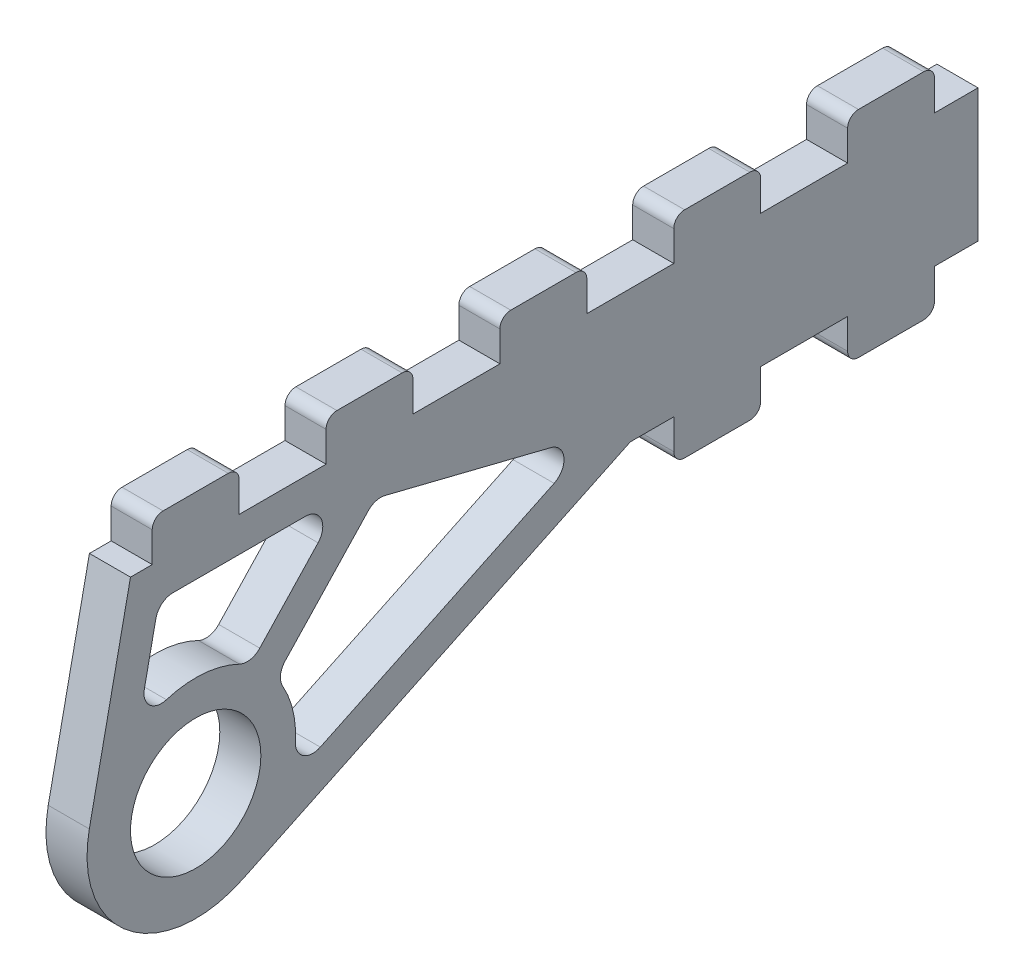
SolidWorks part; units mm, degrees
ref_plane "Front Plane" through (0, 0, 0) normal (0, 0, 1) x (1, 0, 0)
ref_plane "Top Plane" through (0, 0, 0) normal (0, 1, 0) x (1, 0, 0)
ref_plane "Right Plane" through (0, 0, 0) normal (1, 0, 0) x (0, 0, -1)
sketch "Sketch1" plane through (0, 0, 0) normal (1, 0, 0) x (0, 0, -1)
  line L0 (-41.4563, 38.1) -> (38.3452, 38.1) construction
  line L1 (-15.541, 3.2395) -> (-9.525, 32.1)
  line L2 (38.9021, 32.1) -> (-38.9021, 32.1) construction
  line L3 (38.9021, 32.1) -> (38.9021, 38.1) construction
  line L4 (38.9021, 38.1) -> (-38.9021, 38.1) construction
  line L5 (-38.9021, 32.1) -> (-38.9021, 38.1) construction
  line L6 (38.9021, 32.1) -> (-38.9021, 38.1) construction
  line L7 (38.9021, 38.1) -> (-38.9021, 32.1) construction
  line L8 (0, 7.3323) -> (-6.35, 3.6662) construction
  line L9 (-6.35, 3.6662) -> (-6.35, -3.6662) construction
  line L10 (-6.35, -3.6662) -> (0, -7.3323) construction
  line L11 (0, -7.3323) -> (6.35, -3.6662) construction
  line L12 (6.35, -3.6662) -> (6.35, 3.6662) construction
  line L13 (6.35, 3.6662) -> (0, 7.3323) construction
  line L14 (-9.525, 32.1) -> (63.5, 32.1)
  line L15 (0, -15.875) -> (63.5, -15.875)
  line L16 (63.5, -15.875) -> (63.5, 32.1)
  line L18 (157.9971, 6.7) -> (88.9, 6.7) construction
  line L19 (157.9971, 6.7) -> (157.9971, 12.7) construction
  line L20 (157.9971, 12.7) -> (88.9, 12.7) construction
  line L21 (88.9, 6.7) -> (88.9, 12.7) construction
  line L22 (157.9971, 6.7) -> (88.9, 12.7) construction
  line L23 (157.9971, 12.7) -> (88.9, 6.7) construction
  circle A0 centre (0, 0) radius 9.525
  arc A1 (-15.541, 3.2395) -> (0, -15.875) centre (0, 0) ccw
  circle A2 centre (0, 0) radius 25.4 construction
  circle A3 centre (0, 0) radius 6.35 construction
  arc A4 (0, -15.875) -> (-15.541, 3.2395) centre (0, 0) ccw construction
  point P3 (123.4486, 9.7)
  point P7 (0, 35.1)
  point P28 (88.9, 9.7)
  dimension "D1" = 19.05
  dimension "D2" = 6.35
  dimension "D4" = 50.8
  dimension "D3" = 38.1
  dimension "D5" = 6
  dimension "D6" = 12.7
  dimension "D7" = 9.525
  dimension "D8" = 63.5
  dimension "D9" = 25.4
  dimension "D10" = 88.9
extrude "Boss-Extrude1" add sketch "Sketch1" along normal mid plane 6
sketch "Sketch2" plane through (3, 0, 0) normal (1, 0, 0) x (0, 0, -1)
  line L0 (6.8345, -14.3285) -> (63.5, 12.7)
  line L2 (63.5, -15.875) -> (63.5, 32.1) construction
  line L5 (63.5, 12.7) -> (63.5, -15.875)
  line L8 (63.5, -15.875) -> (0, -15.875)
  line L11 (0, -15.875) -> (63.5, -15.875) construction
  line L12 (157.9971, 12.7) -> (88.9, 12.7) construction
  line L22 (0, 0) -> (15.49, 0) construction
  circle A10 centre (0, 0) radius 15.875 construction
  arc A11 (6.8345, -14.3285) -> (0, -15.875) centre (0, 0) cw
  arc A13 (-15.541, 3.2395) -> (0, -15.875) centre (0, 0) ccw construction
extrude "Cut-Extrude1" cut sketch "Sketch2" against normal through all
sketch "Sketch4" plane through (3, 0, 0) normal (1, 0, 0) x (0, 0, -1)
  line L0 (157.9971, 12.7) -> (88.9, 12.7) construction
  line L1 (63.5, 32.1) -> (114.3, 32.1)
  line L2 (63.5, 32.1) -> (63.5, 12.7)
  line L3 (63.5, 12.7) -> (114.3, 12.7)
  line L4 (114.3, 32.1) -> (114.3, 12.7)
  line L5 (88.9, 6.7) -> (88.9, 12.7) construction
  dimension "D1" = 25.4
extrude "Boss-Extrude3" add sketch "Sketch4" against normal up to surface (6 mm away) up to face at (-3, 11.7739, -20.6636)
sketch "Sketch3" plane through (0, 32.1, 0) normal (0, 1, 0) x (1, 0, 0)
  line L0 (3, 114.3) -> (3, -9.525) construction
  line L1 (-3, -6.35) -> (3, -6.35)
  line L2 (-3, -6.35) -> (-3, 6.35)
  line L3 (-3, 6.35) -> (3, 6.35)
  line L4 (3, -6.35) -> (3, 6.35)
  line L5 (-3, -6.35) -> (3, 6.35) construction
  line L6 (-3, 6.35) -> (3, -6.35) construction
  point P0 (0, 0)
  dimension "D1" = 12.7
extrude "Boss-Extrude2" add sketch "Sketch3" along normal blind 6
fillet "Fillet1" radius 1.5875 2 edges at (0, 38.1, -6.35) (0, 38.1, 6.35)
pattern_linear "LPattern1" count 5 spacing 25.4 along (0, 0, -1) of "Boss-Extrude2", "Fillet1"
sketch "Sketch5" plane through (-3, 0, 0) normal (-1, 0, 0) x (0, 0, 1)
  line L0 (-114.3, 12.7) -> (-63.5, 12.7) construction
  line L1 (-69.85, 12.7) -> (-82.55, 12.7)
  line L2 (-69.85, 12.7) -> (-69.85, 6.7)
  line L3 (-69.85, 6.7) -> (-82.55, 6.7)
  line L4 (-82.55, 12.7) -> (-82.55, 6.7)
  line L5 (-69.85, 36.5125) -> (-69.85, 32.1) construction
  line L6 (-82.55, 36.5125) -> (-82.55, 32.1) construction
  dimension "D1" = 6
extrude "Boss-Extrude4" add sketch "Sketch5" against normal up to surface (6 mm away) up to face at (3, 31.7217, -49.7894)
fillet "Fillet2" radius 1.5875 2 edges at (0, 6.7, -69.85) (0, 6.7, -82.55)
pattern_linear "LPattern2" count 2 spacing 25.4 along (0, 0, -1) of "Boss-Extrude4", "Fillet2"
sketch "Sketch6" plane through (3, 0, 0) normal (1, 0, 0) x (0, 0, -1)
  line L0 (-5.3947, 27.02) -> (-10.5678, 2.2029)
  line L1 (4.6474, -9.7434) -> (62.3505, 17.78)
  line L2 (62.3505, 17.78) -> (74.93, 17.78)
  line L3 (74.93, 17.78) -> (74.93, 11.78)
  line L4 (74.93, 11.78) -> (77.47, 11.78)
  line L5 (77.47, 11.78) -> (77.47, 17.78)
  line L6 (77.47, 17.78) -> (100.33, 17.78)
  line L7 (100.33, 17.78) -> (100.33, 11.78)
  line L8 (100.33, 11.78) -> (102.87, 11.78)
  line L9 (102.87, 11.78) -> (102.87, 17.78)
  line L10 (102.87, 17.78) -> (109.22, 17.78)
  line L11 (109.22, 17.78) -> (109.22, 27.02)
  line L12 (109.22, 27.02) -> (102.87, 27.02)
  line L13 (102.87, 27.02) -> (102.87, 33.02)
  line L14 (102.87, 33.02) -> (100.33, 33.02)
  line L15 (100.33, 33.02) -> (100.33, 27.02)
  line L16 (100.33, 27.02) -> (77.47, 27.02)
  line L17 (77.47, 27.02) -> (77.47, 33.02)
  line L18 (77.47, 33.02) -> (74.93, 33.02)
  line L19 (74.93, 33.02) -> (74.93, 27.02)
  line L20 (74.93, 27.02) -> (52.07, 27.02)
  line L21 (52.07, 27.02) -> (52.07, 33.02)
  line L22 (52.07, 33.02) -> (49.53, 33.02)
  line L23 (49.53, 33.02) -> (49.53, 27.02)
  line L24 (49.53, 27.02) -> (26.67, 27.02)
  line L25 (26.67, 27.02) -> (26.67, 33.02)
  line L26 (26.67, 33.02) -> (24.13, 33.02)
  line L27 (24.13, 33.02) -> (24.13, 27.02)
  line L28 (24.13, 27.02) -> (1.27, 27.02)
  line L29 (1.27, 27.02) -> (1.27, 33.02)
  line L30 (1.27, 33.02) -> (-1.27, 33.02)
  line L31 (-1.27, 33.02) -> (-1.27, 27.02)
  line L32 (-1.27, 27.02) -> (-5.3947, 27.02)
  line L33 (95.25, 12.7) -> (95.25, 8.2875)
  line L34 (96.8375, 6.7) -> (106.3625, 6.7)
  line L35 (107.95, 8.2875) -> (107.95, 12.7)
  line L36 (107.95, 12.7) -> (114.3, 12.7)
  line L37 (114.3, 12.7) -> (114.3, 32.1)
  line L38 (114.3, 32.1) -> (107.95, 32.1)
  line L39 (107.95, 32.1) -> (107.95, 36.5125)
  line L40 (106.3625, 38.1) -> (96.8375, 38.1)
  line L41 (95.25, 36.5125) -> (95.25, 32.1)
  line L42 (95.25, 32.1) -> (82.55, 32.1)
  line L43 (82.55, 32.1) -> (82.55, 36.5125)
  line L44 (80.9625, 38.1) -> (71.4375, 38.1)
  line L45 (69.85, 36.5125) -> (69.85, 32.1)
  line L46 (69.85, 32.1) -> (57.15, 32.1)
  line L47 (57.15, 32.1) -> (57.15, 36.5125)
  line L48 (55.5625, 38.1) -> (46.0375, 38.1)
  line L49 (44.45, 36.5125) -> (44.45, 32.1)
  line L50 (44.45, 32.1) -> (31.75, 32.1)
  line L51 (31.75, 32.1) -> (31.75, 36.5125)
  line L52 (30.1625, 38.1) -> (20.6375, 38.1)
  line L53 (19.05, 36.5125) -> (19.05, 32.1)
  line L54 (19.05, 32.1) -> (6.35, 32.1)
  line L55 (6.35, 32.1) -> (6.35, 36.5125)
  line L56 (4.7625, 38.1) -> (-4.7625, 38.1)
  line L57 (-6.35, 36.5125) -> (-6.35, 32.1)
  line L58 (-6.35, 32.1) -> (-9.525, 32.1)
  line L59 (-9.525, 32.1) -> (-15.541, 3.2395)
  line L60 (6.8345, -14.3285) -> (63.5, 12.7)
  line L61 (63.5, 12.7) -> (69.85, 12.7)
  line L62 (69.85, 12.7) -> (69.85, 8.2875)
  line L63 (71.4375, 6.7) -> (80.9625, 6.7)
  line L64 (82.55, 8.2875) -> (82.55, 12.7)
  line L65 (82.55, 12.7) -> (95.25, 12.7)
  line L66 (95.25, 12.7) -> (95.25, 8.2875)
  line L67 (96.8375, 6.7) -> (106.3625, 6.7)
  line L68 (107.95, 8.2875) -> (107.95, 12.7)
  line L69 (107.95, 12.7) -> (114.3, 12.7)
  line L70 (114.3, 12.7) -> (114.3, 32.1)
  line L71 (114.3, 32.1) -> (107.95, 32.1)
  line L72 (107.95, 32.1) -> (107.95, 36.5125)
  line L73 (106.3625, 38.1) -> (96.8375, 38.1)
  line L74 (95.25, 36.5125) -> (95.25, 32.1)
  line L75 (95.25, 32.1) -> (82.55, 32.1)
  line L76 (82.55, 32.1) -> (82.55, 36.5125)
  line L77 (80.9625, 38.1) -> (71.4375, 38.1)
  line L78 (69.85, 36.5125) -> (69.85, 32.1)
  line L79 (69.85, 32.1) -> (57.15, 32.1)
  line L80 (57.15, 32.1) -> (57.15, 36.5125)
  line L81 (55.5625, 38.1) -> (46.0375, 38.1)
  line L82 (44.45, 36.5125) -> (44.45, 32.1)
  line L83 (44.45, 32.1) -> (31.75, 32.1)
  line L84 (31.75, 32.1) -> (31.75, 36.5125)
  line L85 (30.1625, 38.1) -> (20.6375, 38.1)
  line L86 (19.05, 36.5125) -> (19.05, 32.1)
  line L87 (19.05, 32.1) -> (6.35, 32.1)
  line L88 (6.35, 32.1) -> (6.35, 36.5125)
  line L89 (4.7625, 38.1) -> (-4.7625, 38.1)
  line L90 (-6.35, 36.5125) -> (-6.35, 32.1)
  line L91 (-6.35, 32.1) -> (-9.525, 32.1)
  line L92 (-9.525, 32.1) -> (-15.541, 3.2395)
  line L93 (6.8345, -14.3285) -> (63.5, 12.7)
  line L94 (63.5, 12.7) -> (69.85, 12.7)
  line L95 (69.85, 12.7) -> (69.85, 8.2875)
  line L96 (71.4375, 6.7) -> (80.9625, 6.7)
  line L97 (82.55, 8.2875) -> (82.55, 12.7)
  line L98 (82.55, 12.7) -> (95.25, 12.7)
  line L99 (0, 0) -> (25.3883, 27.02) construction
  line L100 (25.3883, 27.02) -> (62.3505, 17.78) construction
  line L101 (1.8511, -1.7393) -> (26.2186, 24.1943)
  line L102 (26.2186, 24.1943) -> (61.7345, 15.3158)
  line L103 (-1.8511, 1.7393) -> (24.5581, 29.8457)
  line L104 (24.5581, 29.8457) -> (62.9665, 20.2442)
  line L105 (-1.27, 27.02) -> (1.27, 27.02)
  circle A0 centre (0, 0) radius 9.525 construction
  circle A1 centre (0, 0) radius 9.525
  arc A2 (-10.5678, 2.2029) -> (4.6474, -9.7434) centre (0, 0) ccw
  arc A3 (74.93, 11.78) -> (74.93, 11.78) centre (74.93, 11.78) ccw
  arc A4 (77.47, 11.78) -> (77.47, 11.78) centre (77.47, 11.78) ccw
  arc A5 (100.33, 11.78) -> (100.33, 11.78) centre (100.33, 11.78) ccw
  arc A6 (102.87, 11.78) -> (102.87, 11.78) centre (102.87, 11.78) ccw
  arc A7 (102.87, 33.02) -> (102.87, 33.02) centre (102.87, 33.02) ccw
  arc A8 (100.33, 33.02) -> (100.33, 33.02) centre (100.33, 33.02) ccw
  arc A9 (77.47, 33.02) -> (77.47, 33.02) centre (77.47, 33.02) ccw
  arc A10 (74.93, 33.02) -> (74.93, 33.02) centre (74.93, 33.02) ccw
  arc A11 (52.07, 33.02) -> (52.07, 33.02) centre (52.07, 33.02) ccw
  arc A12 (49.53, 33.02) -> (49.53, 33.02) centre (49.53, 33.02) ccw
  arc A13 (26.67, 33.02) -> (26.67, 33.02) centre (26.67, 33.02) ccw
  arc A14 (24.13, 33.02) -> (24.13, 33.02) centre (24.13, 33.02) ccw
  arc A15 (95.25, 8.2875) -> (96.8375, 6.7) centre (96.8375, 8.2875) ccw
  arc A16 (106.3625, 6.7) -> (107.95, 8.2875) centre (106.3625, 8.2875) ccw
  arc A17 (107.95, 36.5125) -> (106.3625, 38.1) centre (106.3625, 36.5125) ccw
  arc A18 (96.8375, 38.1) -> (95.25, 36.5125) centre (96.8375, 36.5125) ccw
  arc A19 (82.55, 36.5125) -> (80.9625, 38.1) centre (80.9625, 36.5125) ccw
  arc A20 (71.4375, 38.1) -> (69.85, 36.5125) centre (71.4375, 36.5125) ccw
  arc A21 (57.15, 36.5125) -> (55.5625, 38.1) centre (55.5625, 36.5125) ccw
  arc A22 (46.0375, 38.1) -> (44.45, 36.5125) centre (46.0375, 36.5125) ccw
  arc A23 (31.75, 36.5125) -> (30.1625, 38.1) centre (30.1625, 36.5125) ccw
  arc A24 (20.6375, 38.1) -> (19.05, 36.5125) centre (20.6375, 36.5125) ccw
  arc A25 (6.35, 36.5125) -> (4.7625, 38.1) centre (4.7625, 36.5125) ccw
  arc A26 (-4.7625, 38.1) -> (-6.35, 36.5125) centre (-4.7625, 36.5125) ccw
  arc A27 (-15.541, 3.2395) -> (6.8345, -14.3285) centre (0, 0) ccw
  arc A28 (69.85, 8.2875) -> (71.4375, 6.7) centre (71.4375, 8.2875) ccw
  arc A29 (80.9625, 6.7) -> (82.55, 8.2875) centre (80.9625, 8.2875) ccw
  arc A30 (95.25, 8.2875) -> (96.8375, 6.7) centre (96.8375, 8.2875) ccw
  arc A31 (106.3625, 6.7) -> (107.95, 8.2875) centre (106.3625, 8.2875) ccw
  arc A32 (107.95, 36.5125) -> (106.3625, 38.1) centre (106.3625, 36.5125) ccw
  arc A33 (96.8375, 38.1) -> (95.25, 36.5125) centre (96.8375, 36.5125) ccw
  arc A34 (82.55, 36.5125) -> (80.9625, 38.1) centre (80.9625, 36.5125) ccw
  arc A35 (71.4375, 38.1) -> (69.85, 36.5125) centre (71.4375, 36.5125) ccw
  arc A36 (57.15, 36.5125) -> (55.5625, 38.1) centre (55.5625, 36.5125) ccw
  arc A37 (46.0375, 38.1) -> (44.45, 36.5125) centre (46.0375, 36.5125) ccw
  arc A38 (31.75, 36.5125) -> (30.1625, 38.1) centre (30.1625, 36.5125) ccw
  arc A39 (20.6375, 38.1) -> (19.05, 36.5125) centre (20.6375, 36.5125) ccw
  arc A40 (6.35, 36.5125) -> (4.7625, 38.1) centre (4.7625, 36.5125) ccw
  arc A41 (-4.7625, 38.1) -> (-6.35, 36.5125) centre (-4.7625, 36.5125) ccw
  arc A42 (-15.541, 3.2395) -> (6.8345, -14.3285) centre (0, 0) ccw
  arc A43 (69.85, 8.2875) -> (71.4375, 6.7) centre (71.4375, 8.2875) ccw
  arc A44 (80.9625, 6.7) -> (82.55, 8.2875) centre (80.9625, 8.2875) ccw
  arc A45 (1.27, 33.02) -> (1.27, 33.02) centre (1.27, 33.02) ccw
  arc A46 (-1.27, 33.02) -> (-1.27, 33.02) centre (-1.27, 33.02) ccw
  circle A47 centre (0, 0) radius 14.605
  dimension "D1" = 0
  dimension "D2" = 5.08
  dimension "D3" = 5.08
  dimension "D4" = 2.54
  dimension "D5" = 2.54
extrude "Cut-Extrude2" cut sketch "Sketch6" against normal through all contours A47 L103 L28 L105 L32 L0 | A47 L1 L102 L101
fillet "Fillet3" radius 2.54 8 edges at (0, 8.7422, -11.6996) (0, 24.1943, -26.2186) (0, 16.0622, -58.749) (0, 11.8332, 8.5604) (0, 27.02, 5.3947) (0, 27.02, -21.903) (0, 12.2208, -7.9974) (0, -5.5082, -13.5265)
